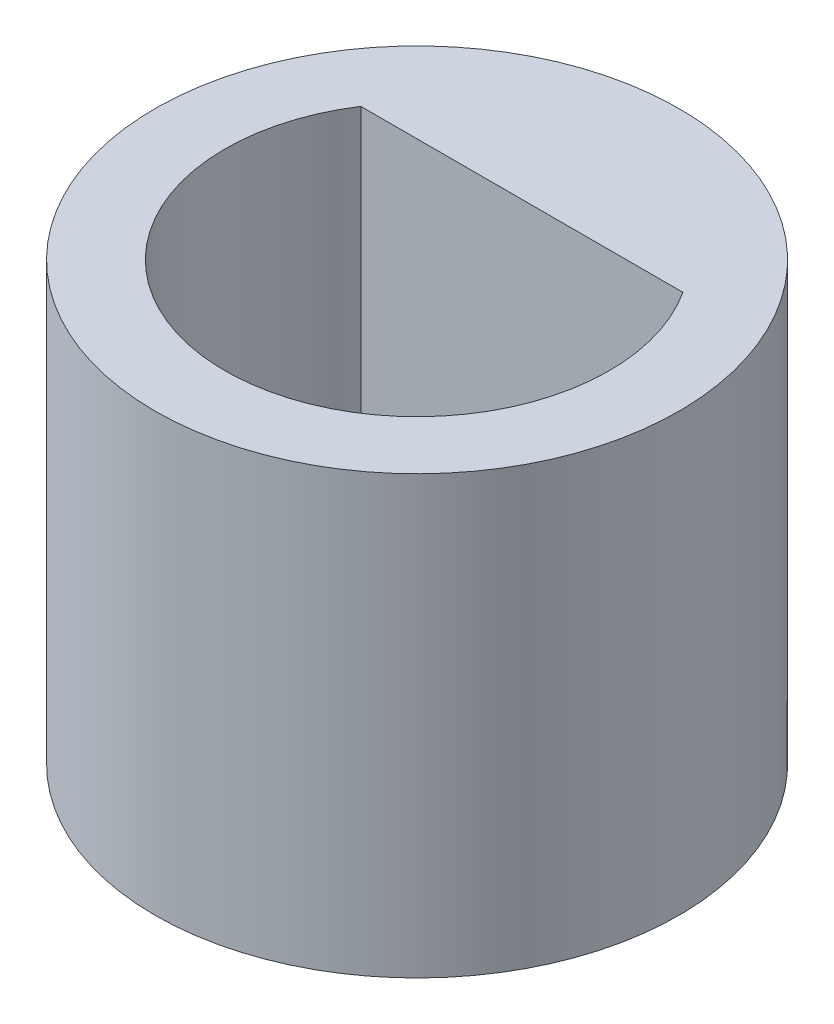
SolidWorks part; units mm, degrees
ref_plane "Front Plane" through (0, 0, 0) normal (0, 0, 1) x (1, 0, 0)
ref_plane "Top Plane" through (0, 0, 0) normal (0, 1, 0) x (1, 0, 0)
ref_plane "Right Plane" through (0, 0, 0) normal (1, 0, 0) x (0, 0, -1)
sketch "Sketch3" plane through (0, 0, 0) normal (0, 1, 0) x (1, 0, 0)
  line L0 (0, 2.2) -> (0, 1.2) construction
  line L1 (-1.8439, 1.2) -> (1.8439, 1.2)
  circle A0 centre (0, 0) radius 3
  arc A1 (-1.8439, 1.2) -> (1.8439, 1.2) centre (0, 0) ccw
  dimension "D1" = 6
  dimension "D2" = 4.4
  dimension "D3" = 1
extrude "Boss-Extrude3" add sketch "Sketch3" along normal blind 5
